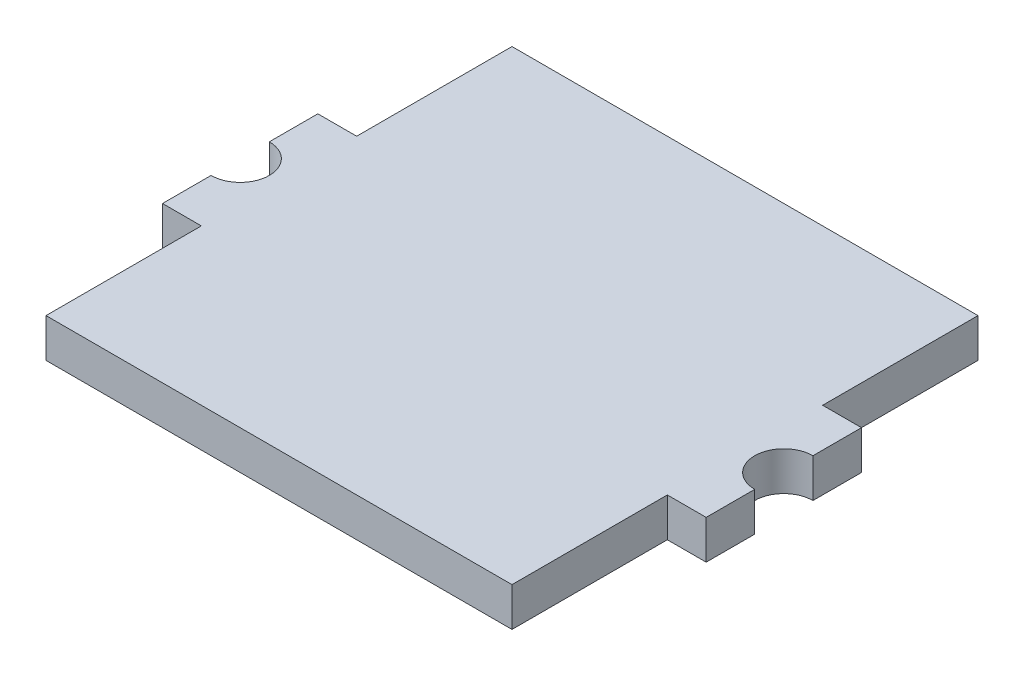
SolidWorks part; units mm, degrees
ref_plane "Front Plane" through (0, 0, 0) normal (0, 0, 1) x (1, 0, 0)
ref_plane "Top Plane" through (0, 0, 0) normal (0, 1, 0) x (1, 0, 0)
ref_plane "Right Plane" through (0, 0, 0) normal (1, 0, 0) x (0, 0, -1)
sketch "Sketch1" plane through (0, 0, 0) normal (0, 1, 0) x (1, 0, 0)
  line L0 (0, 0) -> (0, 12.7)
  line L1 (0, 38.1) -> (38.1, 38.1)
  line L2 (38.1, 38.1) -> (38.1, 25.4)
  line L3 (38.1, 0) -> (0, 0)
  line L4 (0, 25.4) -> (-3.175, 25.4)
  line L5 (-3.175, 25.4) -> (-3.175, 21.4312)
  line L6 (-3.175, 16.6687) -> (-3.175, 12.7)
  line L7 (-3.175, 12.7) -> (0, 12.7)
  line L8 (38.1, 12.7) -> (41.275, 12.7)
  line L9 (41.275, 12.7) -> (41.275, 16.6687)
  line L10 (41.275, 21.4312) -> (41.275, 25.4)
  line L11 (41.275, 25.4) -> (38.1, 25.4)
  line L12 (-3.175, 19.05) -> (0, 19.05) construction
  line L13 (0, 19.05) -> (38.1, 19.05) construction
  line L14 (38.1, 19.05) -> (41.275, 19.05) construction
  line L15 (0, 25.4) -> (0, 38.1)
  line L16 (38.1, 12.7) -> (38.1, 0)
  arc A0 (-3.175, 21.4312) -> (-3.175, 16.6687) centre (-3.175, 19.05) cw
  arc A1 (41.275, 16.6687) -> (41.275, 21.4312) centre (41.275, 19.05) cw
  dimension "D3" = 2.3813
  dimension "D7" = 2.3813
  dimension "D1" = 38.1
  dimension "D2" = 38.1
  dimension "D4" = 19.05
  dimension "D5" = 3.175
  dimension "D6" = 3.175
  dimension "D8" = 6.35
  dimension "D9" = 6.35
extrude "Boss-Extrude1" add sketch "Sketch1" along normal blind 3.175
equation "\"Plywood Thickness\" = 0.125in"
equation "\"D5@Sketch1\"=\"Plywood Thickness\""
equation "\"D6@Sketch1\"=\"Plywood Thickness\""
equation "\"D1@Boss-Extrude1\"=\"Plywood Thickness\""
